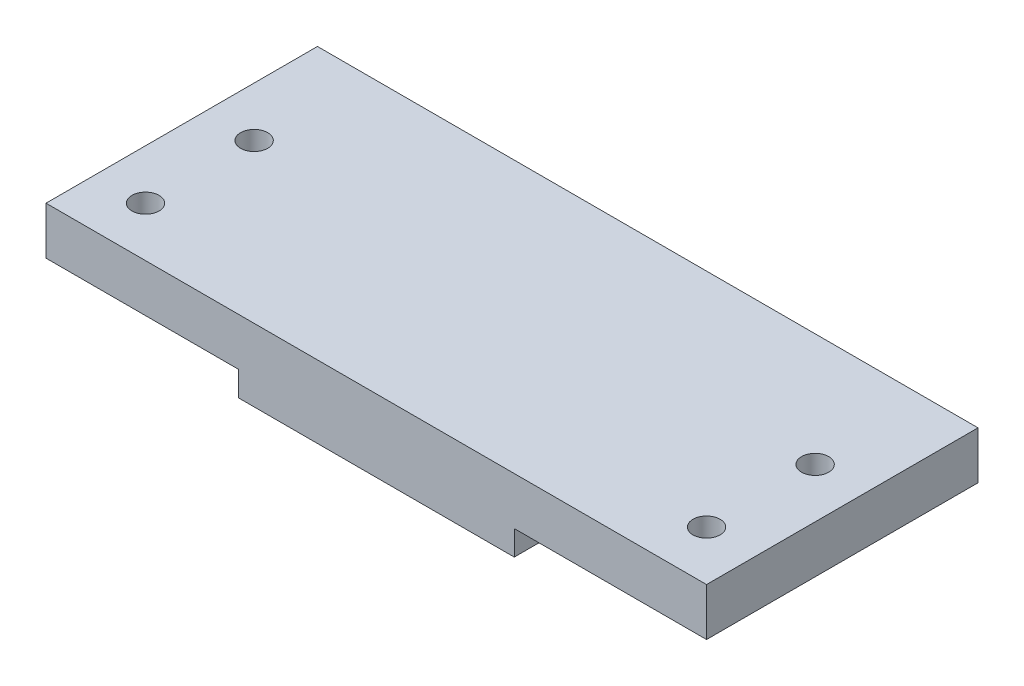
SolidWorks part; units mm, degrees
material "硅橡胶"
ref_plane "前视基准面" through (0, 0, 0) normal (0, 0, 1) x (1, 0, 0)
ref_plane "上视基准面" through (0, 0, 0) normal (0, 1, 0) x (1, 0, 0)
ref_plane "右视基准面" through (0, 0, 0) normal (1, 0, 0) x (0, 0, -1)
sketch "草图1" plane through (0, 0, 0) normal (0, 1, 0) x (1, 0, 0)
  line L1 (-36.5, -15) -> (36.5, -15)
  line L2 (-36.5, -15) -> (-36.5, 15)
  line L3 (-36.5, 15) -> (36.5, 15)
  line L4 (36.5, -15) -> (36.5, 15)
  line L5 (-36.5, -15) -> (36.5, 15) construction
  line L6 (-36.5, 15) -> (36.5, -15) construction
  point P0 (0, 0)
  dimension "D1" = 30
  dimension "D2" = 73
extrude "凸台-拉伸1" add sketch "草图1" along normal blind 8
sketch "草图2" plane through (0, 0, -15) normal (0, 0, -1) x (-1, 0, 0)
  line L0 (0, 0) -> (0, 8) construction
  line L1 (-36.5, 0) -> (-15.25, 0)
  line L2 (-36.5, 0) -> (-36.5, 2.7353)
  line L3 (-36.5, 2.7353) -> (-15.25, 2.7353)
  line L4 (-15.25, 0) -> (-15.25, 2.7353)
  line L5 (-36.5, 0) -> (36.5, 0) construction
  line L6 (-36.5, 8) -> (36.5, 8) construction
  line L7 (36.5, 2.7353) -> (15.25, 2.7353)
  line L8 (15.25, 0) -> (15.25, 2.7353)
  line L9 (36.5, 0) -> (15.25, 0)
  line L10 (36.5, 0) -> (36.5, 2.7353)
  dimension "D1" = 15.25
extrude "切除-拉伸1" cut sketch "草图2" against normal through all
extrude "切除-拉伸2" cut sketch "草图3" against normal mid plane 90
sketch "草图3" plane through (59.2821, -20, -16.5) normal (0, -1, 0) x (1, 0, 0)
  line L0 (-59.2821, -13) -> (-59.2821, 41) construction
  circle A2 centre (-28.2821, 14) radius 1.5
  circle A3 centre (-90.2821, 14) radius 1.5
  circle A6 centre (-90.2821, 26) radius 1.5
  circle A7 centre (-28.2821, 26) radius 1.5
